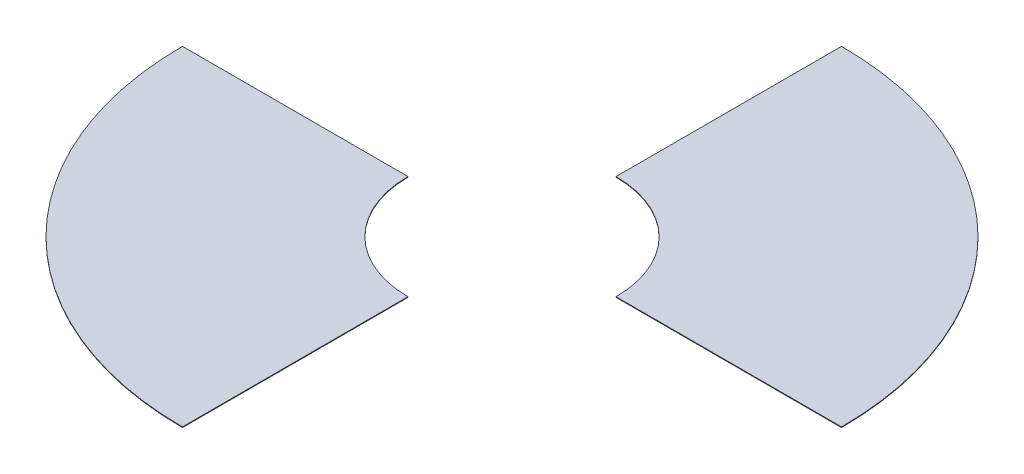
SolidWorks part; units mm, degrees
ref_plane "Front Plane" through (0, 0, 0) normal (0, 0, 1) x (1, 0, 0)
ref_plane "Top Plane" through (0, 0, 0) normal (0, 1, 0) x (1, 0, 0)
ref_plane "Right Plane" through (0, 0, 0) normal (1, 0, 0) x (0, 0, -1)
sketch "Sketch1" plane through (0, 0, 0) normal (0, 1, 0) x (1, 0, 0)
  line L0 (0, 76.2) -> (0, 241.3)
  line L1 (76.2, 0) -> (241.3, 0)
  line L2 (-76.2, 0) -> (-241.3, 0)
  line L3 (0, -76.2) -> (0, -241.3)
  arc A0 (-241.3, 0) -> (0, -241.3) centre (0, 0) ccw
  arc A1 (76.2, 0) -> (0, 76.2) centre (0, 0) ccw
  arc A2 (241.3, 0) -> (0, 241.3) centre (0, 0) ccw
  arc A3 (-76.2, 0) -> (0, -76.2) centre (0, 0) ccw
  dimension "D1" = 482.6
  dimension "D2" = 152.4
extrude "Boss-Extrude1" add sketch "Sketch1" along normal blind 0.508
